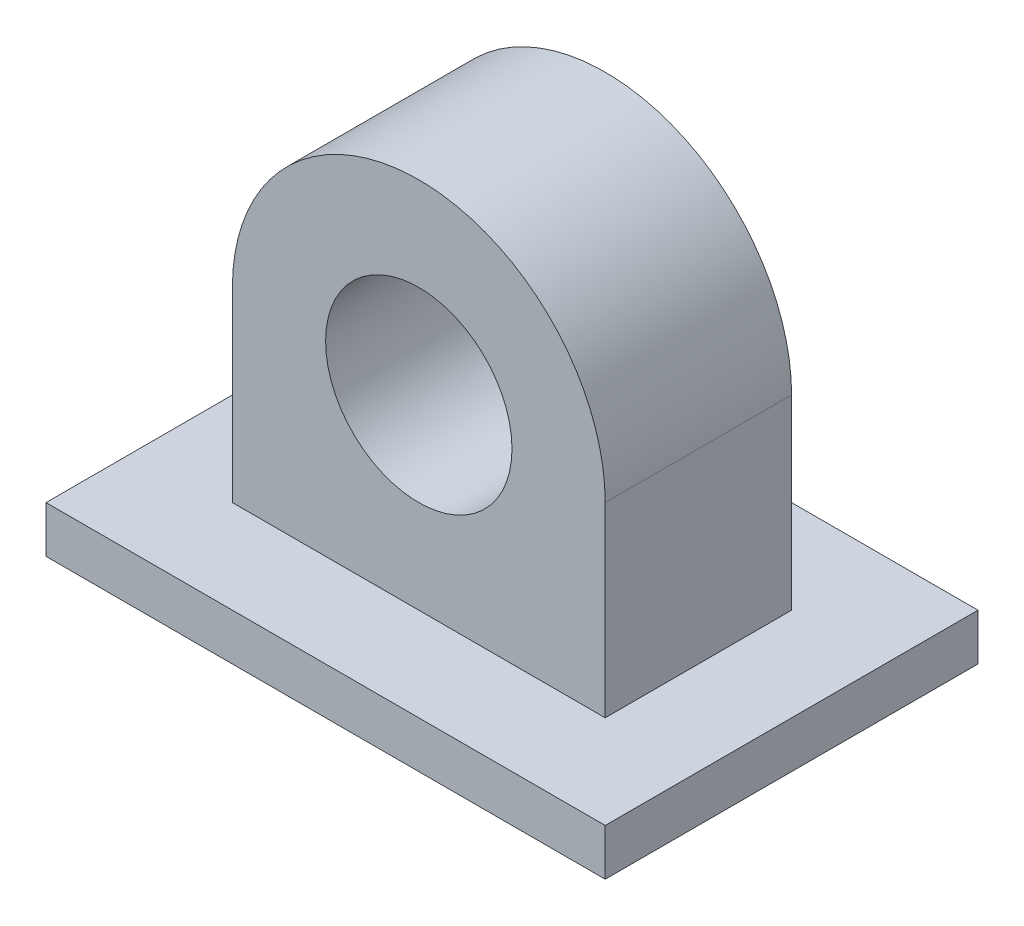
SolidWorks part; units mm, degrees
material "Plain Carbon Steel"
ref_plane "Front Plane" through (0, 0, 0) normal (0, 0, 1) x (1, 0, 0)
ref_plane "Top Plane" through (0, 0, 0) normal (0, 1, 0) x (1, 0, 0)
ref_plane "Right Plane" through (0, 0, 0) normal (1, 0, 0) x (0, 0, -1)
sketch "Sketch1" plane through (0, 0, 0) normal (0, 1, 0) x (1, 0, 0)
  line L1 (-38.1, -25.4) -> (38.1, -25.4)
  line L2 (-38.1, -25.4) -> (-38.1, 25.4)
  line L3 (-38.1, 25.4) -> (38.1, 25.4)
  line L4 (38.1, -25.4) -> (38.1, 25.4)
  line L5 (-38.1, -25.4) -> (38.1, 25.4) construction
  line L6 (-38.1, 25.4) -> (38.1, -25.4) construction
  point P0 (0, 0)
  dimension "D1" = 50.8
  dimension "D2" = 76.2
extrude "Boss-Extrude1" add sketch "Sketch1" along normal blind 6.35
sketch "Sketch2" plane through (0, 0, 0) normal (0, 0, 1) x (1, 0, 0)
  line L0 (-38.1, 6.35) -> (38.1, 6.35) construction
  line L1 (-25.4, 6.35) -> (25.4, 6.35)
  line L2 (-25.4, 6.35) -> (-25.4, 31.75)
  line L3 (-25.4, 31.75) -> (25.4, 31.75)
  line L4 (25.4, 6.35) -> (25.4, 31.75)
  line L5 (-25.4, 6.35) -> (-38.1, 6.35) construction
  line L8 (38.1, 6.35) -> (25.4, 6.35) construction
  arc A0 (-25.4, 31.75) -> (25.4, 31.75) centre (0, 31.75) cw
  dimension "D1" = 50.8
  dimension "D2" = 25.4
extrude "Boss-Extrude2" add sketch "Sketch2" along normal mid plane 25.4 contours A0 L3 | L1 L4 L3 L2
sketch "Sketch3" plane through (0, 0, 12.7) normal (0, 0, 1) x (1, 0, 0)
  circle A0 centre (0, 31.75) radius 12.7
  dimension "D1" = 25.4
extrude "Cut-Extrude1" cut sketch "Sketch3" against normal through all
sketch "Sketch4" plane through (0, 6.35, 0) normal (0, 1, 0) x (1, 0, 0)
  line L0 (-38.1, 25.4) -> (-38.1, -25.4) construction
  line L1 (38.1, 25.4) -> (-38.1, 25.4) construction
  line L2 (38.1, -25.4) -> (38.1, 25.4) construction
  line L3 (-38.1, -25.4) -> (38.1, -25.4) construction
  point P0 (-31.75, 19.05)
  point P1 (31.75, 19.05)
  point P2 (31.75, -19.05)
  point P3 (-31.75, -19.05)
  dimension "D1" = 6.35
  dimension "D2" = 6.35
  dimension "D3" = 6.35
  dimension "D4" = 6.35
